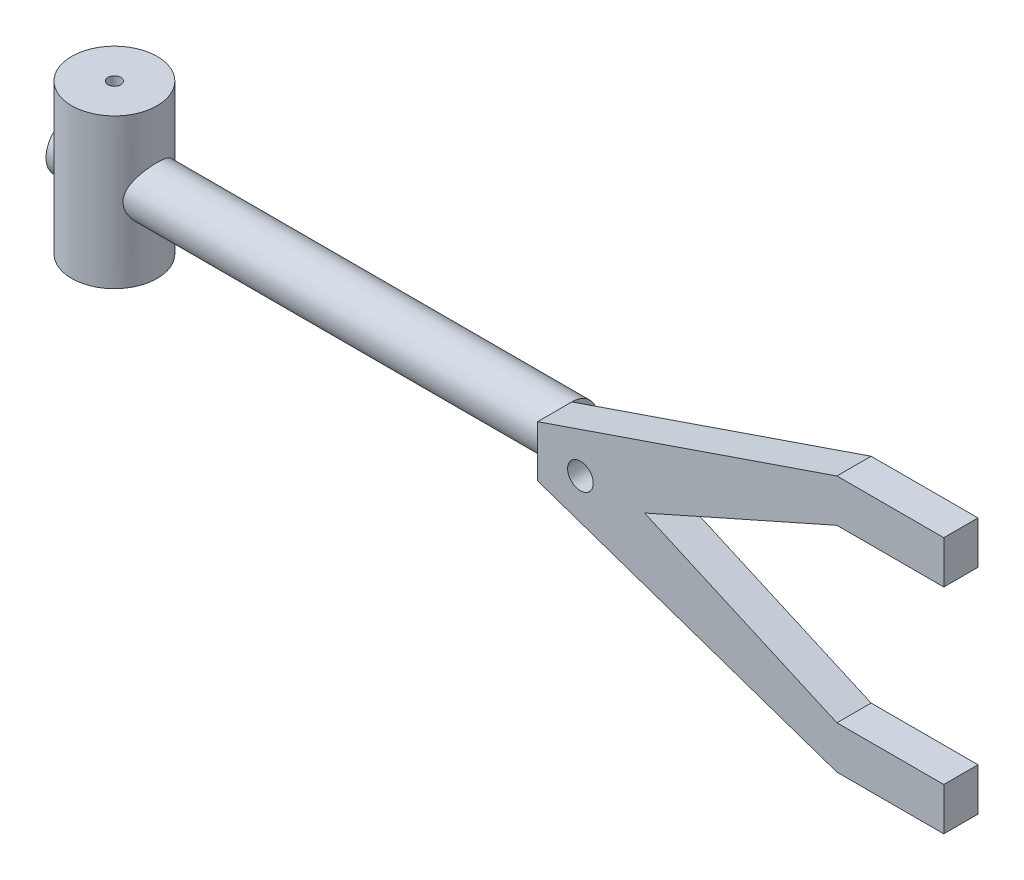
SolidWorks part; units mm, degrees
ref_plane "GAUCHE" through (0, 0, 0) normal (0, 0, 1) x (1, 0, 0)
ref_plane "Plan2" through (0, 0, 0) normal (0, 1, 0) x (1, 0, 0)
ref_plane "Plan3" through (0, 0, 0) normal (1, 0, 0) x (0, 0, -1)
sketch "Esquisse1" plane through (0, 0, 0) normal (0, 0, 1) x (1, 0, 0)
  line L0 (0, 6) -> (0, -6)
  line L1 (0, 6) -> (70, 30)
  line L2 (70, 30) -> (95, 30)
  line L3 (95, 30) -> (95, 20)
  line L4 (95, 20) -> (70, 20)
  line L5 (70, 20) -> (25, 0)
  line L6 (25, 0) -> (70, -20)
  line L7 (70, -20) -> (95, -20)
  line L8 (95, -20) -> (95, -30)
  line L9 (95, -30) -> (70, -30)
  line L10 (70, -30) -> (0, -6)
  line L11 (-13, 0) -> (13, 0) construction
  circle A0 centre (10, 0) radius 3
  dimension "D7" = 6
  dimension "D1" = 12
  dimension "D2" = 60
  dimension "D3" = 25
  dimension "D4" = 10
  dimension "D5" = 95
  dimension "D6" = 70
  dimension "D8" = 10
extrude "Base-Extrusion" add sketch "Esquisse1" along normal blind 8
sketch "Esquisse2" plane through (0, 0, 0) normal (-1, 0, 0) x (0, 0, 1)
  circle A0 centre (0, 0) radius 6
  dimension "D1" = 12
extrude "Boss.-Extru.1" add sketch "Esquisse2" along normal blind 117
sketch "Esquisse3" plane through (0, 0, 0) normal (0, 1, 0) x (1, 0, 0)
  line L1 (-117, 0) -> (0, 0) construction
  line L2 (-117, 6) -> (-117, -6) construction
  circle A0 centre (-107, 0) radius 10
  dimension "D1" = 20
  dimension "D2" = 10
extrude "Boss.-Extru.2" add sketch "Esquisse3" along normal mid plane 35
sketch "Esquisse4" plane through (0, 17.5, 0) normal (0, 1, 0) x (-1, 0, 0)
  line L0 (137.1722, 0) -> (76.6556, 0) construction
  circle A0 centre (107, 0) radius 1.5
  circle A1 centre (107, 0) radius 10 construction
  dimension "D1" = 3
extrude "Enlèv. mat.-Extru.1" cut sketch "Esquisse4" against normal blind 35
